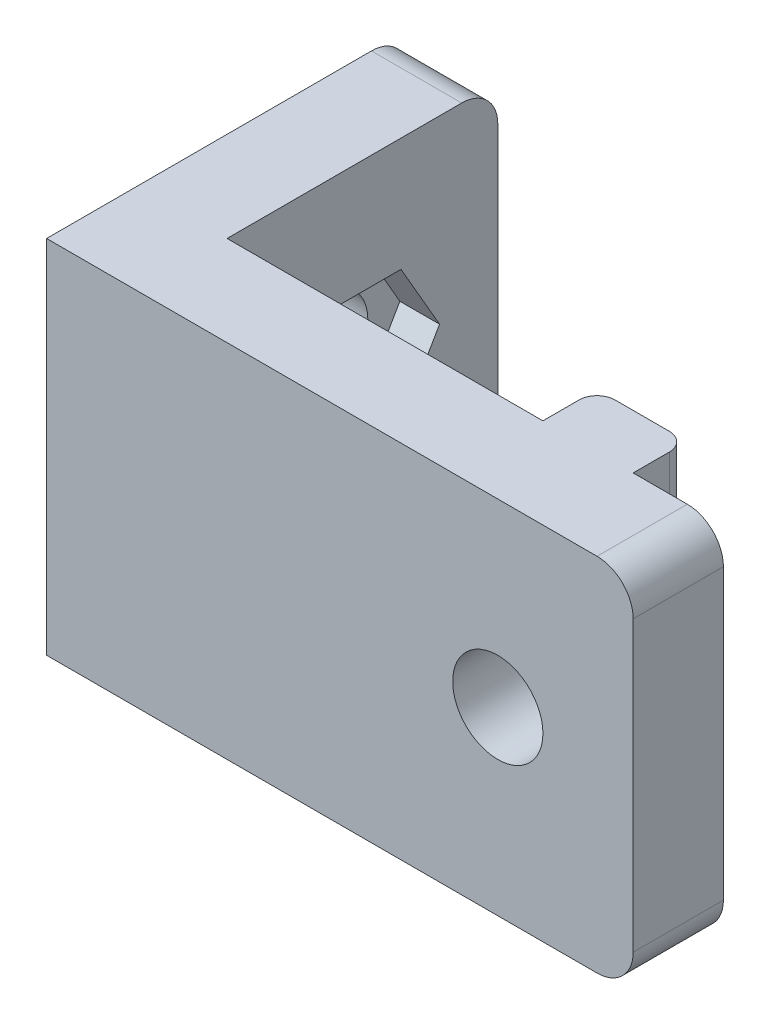
SolidWorks part; units mm, degrees
ref_plane "Front Plane" through (0, 0, 0) normal (0, 0, 1) x (1, 0, 0)
ref_plane "Top Plane" through (0, 0, 0) normal (0, 1, 0) x (1, 0, 0)
ref_plane "Right Plane" through (0, 0, 0) normal (1, 0, 0) x (0, 0, -1)
sketch "Sketch1" plane through (0, 0, 0) normal (0, 0, 1) x (1, 0, 0)
  line L1 (16.25, -10) -> (-16.25, -10)
  line L2 (16.25, -10) -> (16.25, 10)
  line L3 (16.25, 10) -> (-16.25, 10)
  line L4 (-16.25, -10) -> (-16.25, 10)
  line L5 (16.25, -10) -> (-16.25, 10) construction
  line L6 (16.25, 10) -> (-16.25, -10) construction
  point P0 (0, 0)
  dimension "D1" = 20
  dimension "D2" = 32.5
extrude "Boss-Extrude1" add sketch "Sketch1" along normal blind 5
sketch "Sketch2" plane through (0, 0, 0) normal (0, 0, -1) x (-1, 0, 0)
  line L0 (16.25, -10) -> (-16.25, -10) construction
  line L1 (16.25, 10) -> (11.25, 10)
  line L2 (16.25, 10) -> (16.25, -10)
  line L3 (16.25, -10) -> (11.25, -10)
  line L4 (11.25, 10) -> (11.25, -10)
  dimension "D1" = 5
extrude "Boss-Extrude2" add sketch "Sketch2" along normal blind 15
sketch "Sketch3" plane through (-11.25, 0, 0) normal (1, 0, 0) x (0, 0, -1)
  circle A0 centre (7.5, 0) radius 2.5
extrude "Cut-Extrude1" cut sketch "Sketch3" against normal blind 15
sketch "Sketch4" plane through (0, 0, 5) normal (0, 0, 1) x (1, 0, 0)
  line L0 (16.25, -10) -> (16.25, 10) construction
  circle A0 centre (8.75, 0) radius 2.5
  dimension "D1" = 7.5
extrude "Cut-Extrude2" cut sketch "Sketch4" against normal blind 15
sketch "Sketch5" plane through (0, 0, 0) normal (0, 0, -1) x (-1, 0, 0)
  line L0 (-16.25, 10) -> (11.25, 10) construction
  line L1 (-11.25, 10) -> (-6.25, 10)
  line L2 (-11.25, 10) -> (-11.25, 6)
  line L3 (-11.25, 6) -> (-6.25, 6)
  line L4 (-6.25, 10) -> (-6.25, 6)
  line L5 (55, 0) -> (-55, 0) construction
  line L6 (-6.25, -10) -> (-6.25, -6)
  line L7 (-11.25, -6) -> (-6.25, -6)
  line L8 (-11.25, -10) -> (-11.25, -6)
  line L9 (-11.25, -10) -> (-6.25, -10)
  circle A0 centre (-8.75, 0) radius 2.5 construction
  point P6 (-8.75, 6)
  dimension "D1" = 4
  dimension "D2" = 5
  dimension "D3" = 0
extrude "Boss-Extrude3" add sketch "Sketch5" along normal blind 3
fillet "Fillet1" radius 1 4 edges at (6.25, -8, -3) (11.25, -8, -3) (6.25, 8, -3) (11.25, 8, -3)
fillet "Fillet2" radius 2 4 edges at (-13.75, 10, -15) (-13.75, -10, -15) (16.25, 10, 2.5) (16.25, -10, 2.5)
sketch "Sketch6" plane through (-11.25, 0, 0) normal (1, 0, 0) x (0, 0, -1)
  line L1 (3.2276, 0) -> (5.3638, -3.7)
  line L2 (5.3638, -3.7) -> (9.6362, -3.7)
  line L3 (9.6362, -3.7) -> (11.7724, 0)
  line L4 (11.7724, 0) -> (9.6362, 3.7)
  line L5 (9.6362, 3.7) -> (5.3638, 3.7)
  line L6 (5.3638, 3.7) -> (3.2276, 0)
  circle A0 centre (7.5, 0) radius 3.7 construction
  dimension "D1" = 7.4
extrude "Cut-Extrude3" cut sketch "Sketch6" against normal blind 2.2
